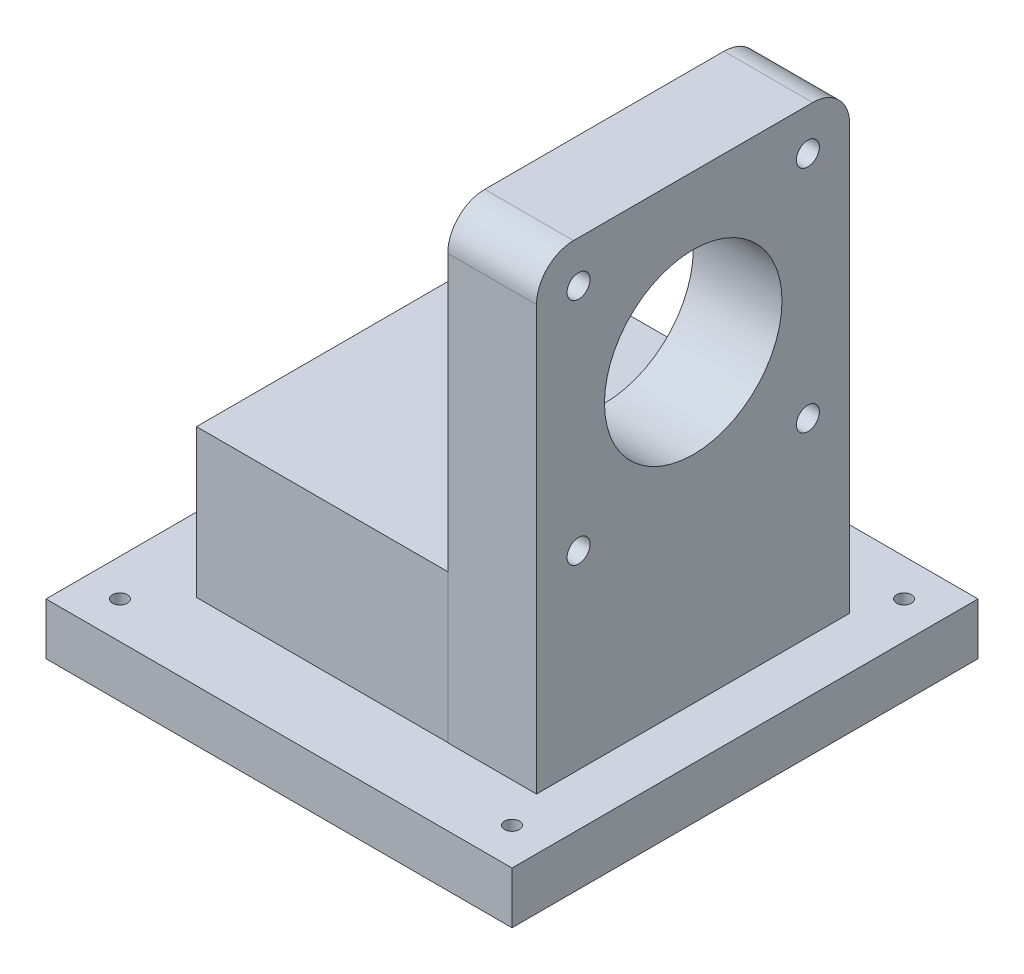
SolidWorks part; units mm, degrees
ref_plane "Front Plane" through (0, 0, 0) normal (0, 0, 1) x (1, 0, 0)
ref_plane "Top Plane" through (0, 0, 0) normal (0, 1, 0) x (1, 0, 0)
ref_plane "Right Plane" through (0, 0, 0) normal (1, 0, 0) x (0, 0, -1)
sketch "Sketch1" plane through (0, 0, 0) normal (0, 1, 0) x (1, 0, 0)
  line L1 (-27, -31.5) -> (36, -31.5)
  line L2 (-27, -31.5) -> (-27, 31.5)
  line L3 (-27, 31.5) -> (36, 31.5)
  line L4 (36, -31.5) -> (36, 31.5)
  line L5 (-27, -31.5) -> (36, 31.5) construction
  line L6 (-27, 31.5) -> (36, -31.5) construction
  point P0 (4.5, 0)
  dimension "D1" = 63
  dimension "D2" = 63
  dimension "D3" = 31.5
  dimension "D4" = 27
extrude "Base Plate" add sketch "Sketch1" along normal blind 7
sketch "Sketch4" plane through (0, 7, 0) normal (0, 1, 0) x (1, 0, 0)
  line L1 (-17, -21.15) -> (17, -21.15)
  line L2 (-17, -21.15) -> (-17, 21.15)
  line L3 (-17, 21.15) -> (17, 21.15)
  line L4 (17, -21.15) -> (17, 21.15)
  line L5 (-17, -21.15) -> (17, 21.15) construction
  line L6 (-17, 21.15) -> (17, -21.15) construction
  point P0 (0, 0)
  dimension "D1" = 34
  dimension "D2" = 42.3
extrude "Main Support" add sketch "Sketch4" along normal blind 20
sketch "Sketch5" plane through (0, 7, 0) normal (0, 1, 0) x (1, 0, 0)
  line L1 (17, 21.15) -> (29, 21.15)
  line L2 (17, 21.15) -> (17, -21.185)
  line L3 (17, -21.185) -> (29, -21.185)
  line L4 (29, 21.15) -> (29, -21.185)
  dimension "D1" = 12
extrude "Screw Support" add sketch "Sketch5" along normal blind 62.3
sketch "Sketch6" plane through (29, 0, 0) normal (1, 0, 0) x (0, 0, -1)
  line L0 (21.15, 27) -> (-21.15, 27) construction
  line L1 (21.15, 27) -> (-21.15, 27)
  circle A0 centre (-15.5, 32.65) radius 1.555
  circle A1 centre (15.5, 32.65) radius 1.555
  circle A2 centre (15.5, 63.65) radius 1.555
  circle A3 centre (-15.5, 63.65) radius 1.555
  circle A4 centre (0, 48.15) radius 12
  dimension "D1" = 3.11
  dimension "D2" = 3.11
  dimension "D3" = 3.11
  dimension "D4" = 3.11
  dimension "D5" = 24
  dimension "D7" = 31
  dimension "D8" = 15.5
  dimension "D9" = 31
  dimension "D10" = 15.5
  dimension "D6" = 21.15
extrude "Screw" cut sketch "Sketch6" against normal blind 50 contours A4 | A0 | A1 | A2 | A3
fillet "Screw Support Fillet" radius 5 2 edges at (23, 69.3, -21.15) (23, 69.3, 21.185)
sketch "Sketch7" plane through (0, 7, 0) normal (0, 1, 0) x (1, 0, 0)
  line L0 (-27, 31.5) -> (-27, -31.5) construction
  line L1 (36, 31.5) -> (-27, 31.5) construction
  line L2 (36, -31.5) -> (36, 31.5) construction
  line L3 (-27, -31.5) -> (36, -31.5) construction
  circle A0 centre (-22, 26.5) radius 1
  circle A1 centre (31, 26.5) radius 1
  circle A2 centre (31, -26.5) radius 1
  circle A3 centre (-22, -26.5) radius 1
  dimension "D1" = 2
  dimension "D2" = 2
  dimension "D3" = 2
  dimension "D4" = 2
  dimension "D5" = 5
  dimension "D6" = 5
  dimension "D7" = 5
  dimension "D8" = 5
extrude "Base Screw" cut sketch "Sketch7" against normal up to next
